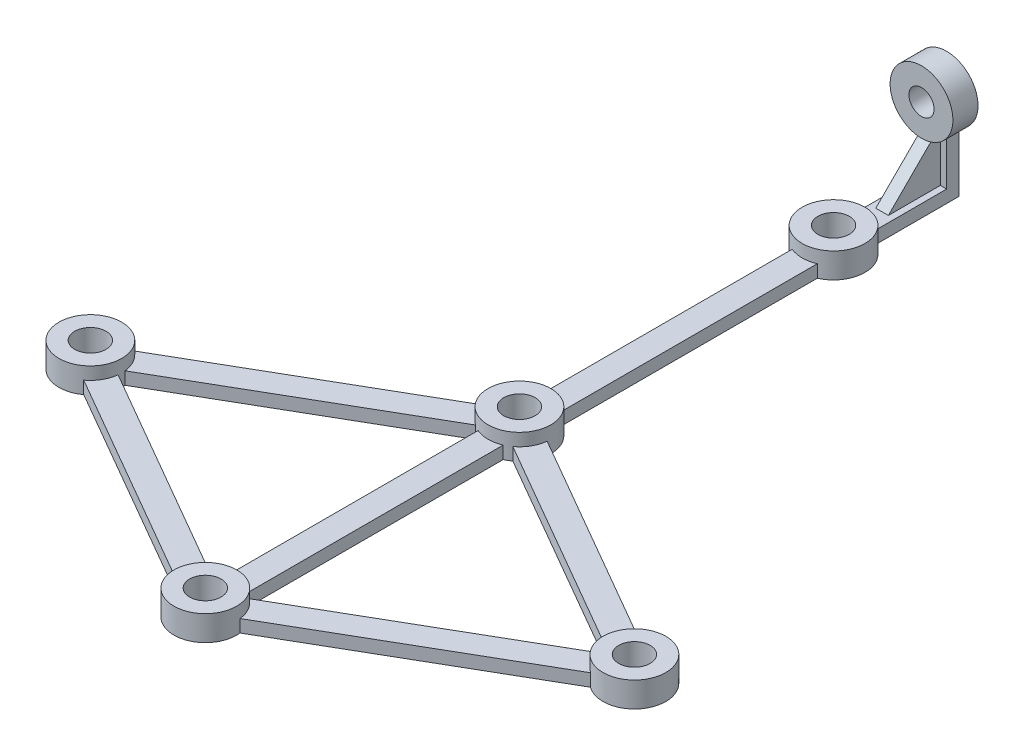
SolidWorks part; units mm, degrees
ref_plane "Спереди" through (0, 0, 0) normal (0, 0, 1) x (1, 0, 0)
ref_plane "Сверху" through (0, 0, 0) normal (0, 1, 0) x (1, 0, 0)
ref_plane "Справа" through (0, 0, 0) normal (1, 0, 0) x (0, 0, -1)
sketch "Эскиз3" plane through (0, 0, 0) normal (0, 1, 0) x (1, 0, 0)
  line L0 (0, 0.2535) -> (0, 129.6974) construction
  line L2 (-2, 168) -> (2, 168)
  line L3 (-2, 168) -> (-2, 48)
  line L4 (-2, 48) -> (2, 48)
  line L5 (2, 168) -> (2, 48)
  line L6 (-2, 168) -> (2, 48) construction
  line L7 (-2, 48) -> (2, 168) construction
  point P1 (0, 108)
  dimension "D1" = 4
  dimension "D2" = 120
extrude "Бобышка-Вытянуть2" add sketch "Эскиз3" along normal blind 2
sketch "Эскиз4" plane through (0, 0, 0) normal (0, 1, 0) x (1, 0, 0)
  line L0 (0, 0) -> (0, 202.0606) construction
  circle A0 centre (0, 52) radius 5
  circle A1 centre (0, 102) radius 5
  circle A2 centre (0, 152) radius 5
  dimension "D1" = 52
  dimension "D2" = 50
  dimension "D3" = 50
extrude "Бобышка-Вытянуть3" add sketch "Эскиз4" along normal blind 4
sketch "Эскиз9" plane through (0, 0, 0) normal (0, 1, 0) x (1, 0, 0)
  line L0 (0, 141.0472) -> (0, 14.3903) construction
  circle A0 centre (-43.3013, 77) radius 5
  circle A1 centre (0, 102) radius 5 construction
  circle A2 centre (0, 52) radius 5 construction
  circle A3 centre (43.3013, 77) radius 5
  dimension "D1" = 50
  dimension "D2" = 50
extrude "Бобышка-Вытянуть7" add sketch "Эскиз9" along normal blind 4 separate body
sketch "Эскиз10" plane through (0, 0, 0) normal (0, 1, 0) x (1, 0, 0)
  line L0 (0, 102) -> (-43.3013, 77) construction
  line L1 (-43.3013, 77) -> (0, 52) construction
  line L2 (0, 52) -> (43.3013, 77) construction
  line L3 (43.3013, 77) -> (0, 102) construction
  line L4 (0, 104.3094) -> (-47.3013, 77)
  line L5 (-47.3013, 77) -> (0, 49.6906)
  line L6 (0, 49.6906) -> (47.3013, 77)
  line L7 (47.3013, 77) -> (0, 104.3094)
  line L8 (0, 99.6906) -> (-39.3013, 77)
  line L9 (-39.3013, 77) -> (0, 54.3094)
  line L10 (0, 54.3094) -> (39.3013, 77)
  line L11 (39.3013, 77) -> (0, 99.6906)
  dimension "D1" = 2
  dimension "D2" = 2
extrude "Бобышка-Вытянуть8" add sketch "Эскиз10" along normal blind 2
sketch "Эскиз5" plane through (0, 0, 0) normal (0, 1, 0) x (1, 0, 0)
  circle A0 centre (0, 102) radius 2.5
  circle A1 centre (0, 52) radius 2.5
  circle A2 centre (0, 152) radius 2.5
  circle A3 centre (-43.3013, 77) radius 2.5
  circle A4 centre (43.3013, 77) radius 2.5
extrude "Вырез-Вытянуть3" cut sketch "Эскиз5" along normal through all
sketch "Эскиз11" plane through (0, 0, 0) normal (0, 1, 0) x (1, 0, 0)
  line L0 (0, 170) -> (0, 168) construction
  line L1 (-2, 168) -> (2, 168)
  line L2 (-2, 168) -> (-2, 170)
  line L3 (-2, 170) -> (2, 170)
  line L4 (2, 168) -> (2, 170)
  line L5 (0, 167.1635) -> (0, 171.5139) construction
  dimension "D1" = 2
  dimension "D2" = 4
extrude "Бобышка-Вытянуть9" add sketch "Эскиз11" along normal blind 10
sketch "Эскиз12" plane through (0, 0, -170) normal (0, 0, -1) x (-1, 0, 0)
  circle A0 centre (0, 14) radius 5
  dimension "D1" = 14
extrude "Бобышка-Вытянуть10" add sketch "Эскиз12" against normal blind 4
sketch "Эскиз13" plane through (0, 0, -170) normal (0, 0, -1) x (-1, 0, 0)
  circle A0 centre (0, 14) radius 2
extrude "Вырез-Вытянуть4" cut sketch "Эскиз13" against normal up to next
sketch "Эскиз15" plane through (0, 0, 0) normal (1, 0, 0) x (0, 0, -1)
  line L0 (166.4601, 8.7373) -> (160.2869, 2.564)
rib "Ребро2" sketch "Эскиз15" sketch "Эскиз15" thickness 2 extrusion direction parallel to sketch draft on no parameters "D1"=2
